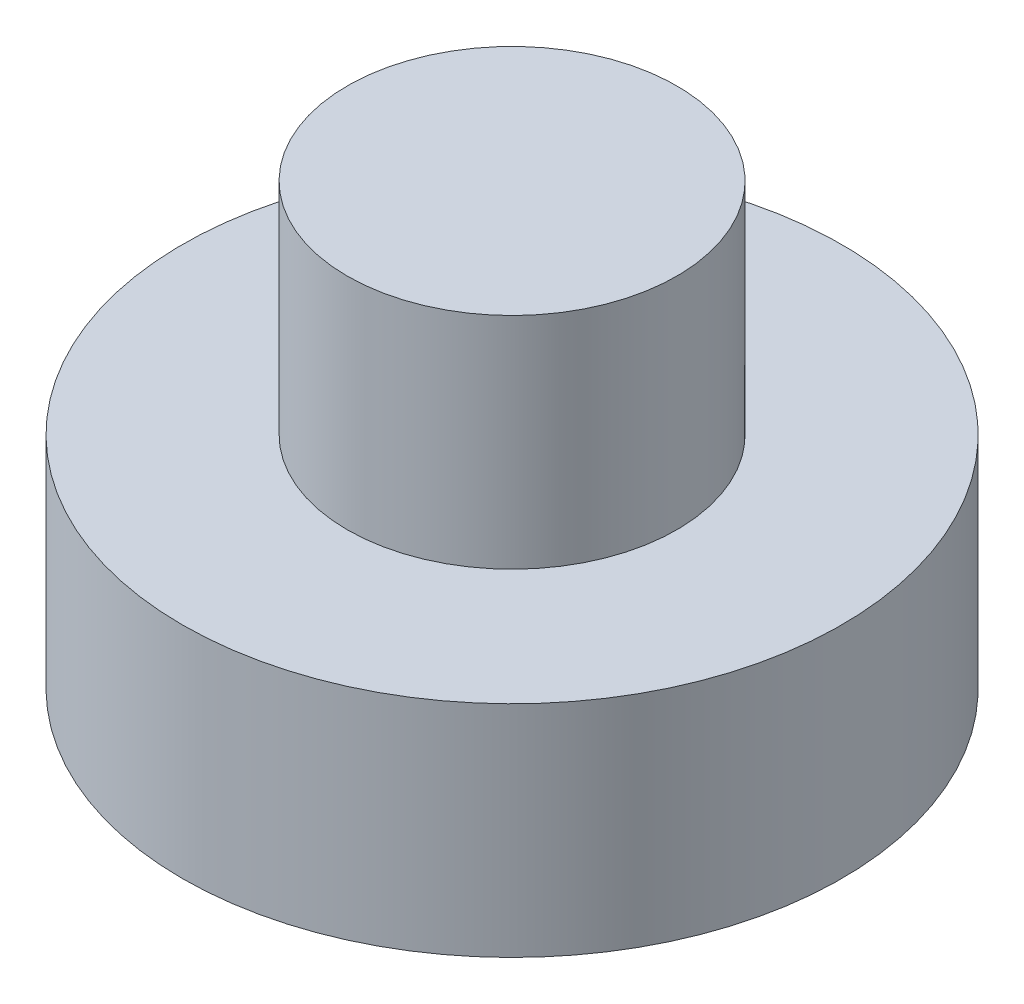
SolidWorks part; units mm, degrees
ref_plane "Спереди" through (0, 0, 0) normal (0, 0, 1) x (1, 0, 0)
ref_plane "Сверху" through (0, 0, 0) normal (0, 1, 0) x (1, 0, 0)
ref_plane "Справа" through (0, 0, 0) normal (1, 0, 0) x (0, 0, -1)
sketch "Эскиз1" plane through (0, 0, 0) normal (0, 1, 0) x (1, 0, 0)
  circle A0 centre (0, 0) radius 30
  dimension "D1" = 60
extrude "Бобышка-Вытянуть1" add sketch "Эскиз1" along normal blind 20
sketch "Эскиз2" plane through (0, 20, 0) normal (0, 1, 0) x (1, 0, 0)
  circle A0 centre (0, 0) radius 15
  dimension "D1" = 30
extrude "Бобышка-Вытянуть2" add sketch "Эскиз2" along normal blind 20
